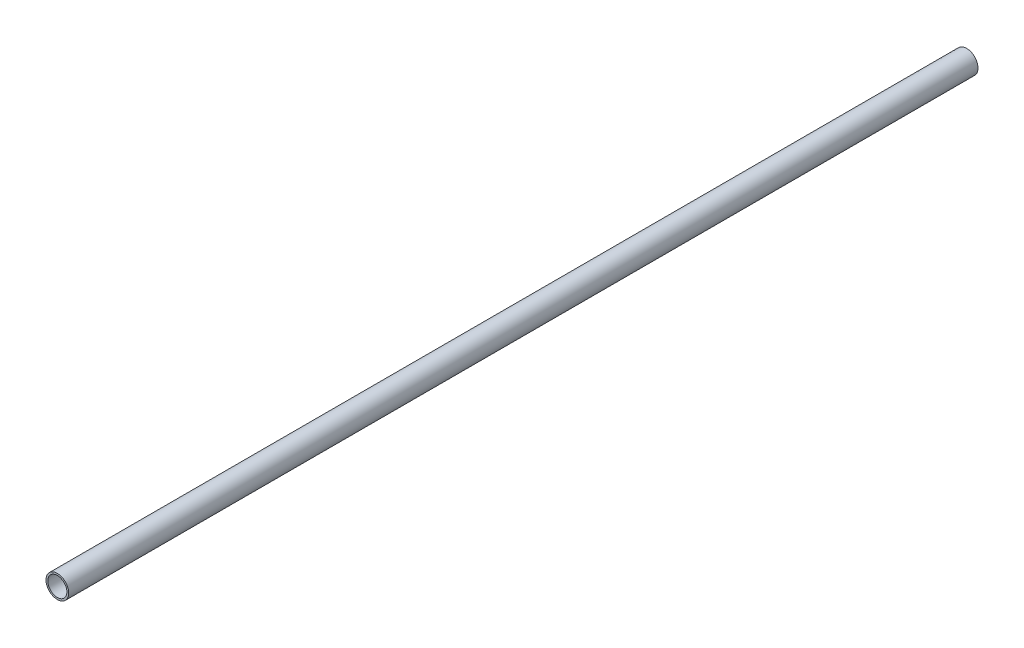
SolidWorks part; units mm, degrees
material "Hexcel AS4C (3000 Filaments)"
ref_plane "Front Plane" through (0, 0, 0) normal (0, 0, 1) x (1, 0, 0)
ref_plane "Top Plane" through (0, 0, 0) normal (0, 1, 0) x (1, 0, 0)
ref_plane "Right Plane" through (0, 0, 0) normal (1, 0, 0) x (0, 0, -1)
sketch "Sketch1" plane through (0, 0, 0) normal (0, 0, 1) x (1, 0, 0)
  circle A0 centre (0, 0) radius 10.5
  circle A1 centre (0, 0) radius 12.5
  dimension "D1" = 25
  dimension "D2" = 21
extrude "Boss-Extrude1" add sketch "Sketch1" along normal blind 1000
